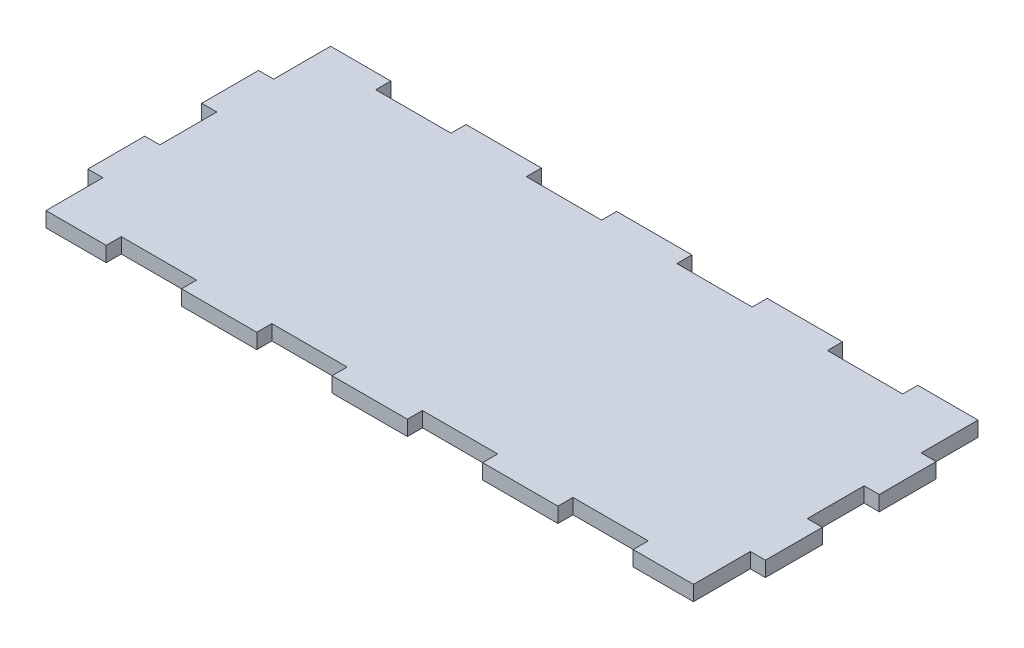
SolidWorks part; units mm, degrees
ref_plane "Front Plane" through (0, 0, 0) normal (0, 0, 1) x (1, 0, 0)
ref_plane "Top Plane" through (0, 0, 0) normal (0, 1, 0) x (1, 0, 0)
ref_plane "Right Plane" through (0, 0, 0) normal (1, 0, 0) x (0, 0, -1)
sketch "Sketch1" plane through (0, 0, 0) normal (0, 1, 0) x (1, 0, 0)
  line L1 (-57.15, 24.003) -> (57.15, 24.003)
  line L2 (-57.15, 24.003) -> (-57.15, -24.003)
  line L3 (-57.15, -24.003) -> (57.15, -24.003)
  line L4 (57.15, 24.003) -> (57.15, -24.003)
  line L5 (-57.15, 24.003) -> (57.15, -24.003) construction
  line L6 (-57.15, -24.003) -> (57.15, 24.003) construction
  point P0 (0, 0)
  dimension "D1" = 48.006
  dimension "D2" = 114.3
extrude "Boss-Extrude1" add sketch "Sketch1" along normal blind 2.54
sketch "Sketch2" plane through (0, 2.54, 0) normal (0, 1, 0) x (1, 0, 0)
  line L0 (57.15, -14.4018) -> (54.61, -14.4018)
  line L1 (57.15, -24.003) -> (57.15, 24.003) construction
  line L2 (54.61, -14.4018) -> (54.61, -24.003)
  line L3 (54.61, -24.003) -> (44.45, -24.003)
  line L4 (44.45, -24.003) -> (44.45, -21.463)
  line L5 (44.45, -21.463) -> (31.75, -21.463)
  line L6 (31.75, -21.463) -> (31.75, -24.003)
  line L7 (-57.15, -24.003) -> (57.15, -24.003) construction
  line L8 (31.75, -24.003) -> (19.05, -24.003)
  line L9 (19.05, -24.003) -> (19.05, -21.463)
  line L10 (19.05, -21.463) -> (6.35, -21.463)
  line L11 (6.35, -21.463) -> (6.35, -24.003)
  line L12 (6.35, -24.003) -> (-6.35, -24.003)
  line L13 (-6.35, -24.003) -> (-6.35, -21.463)
  line L14 (-6.35, -21.463) -> (-19.05, -21.463)
  line L15 (-19.05, -21.463) -> (-19.05, -24.003)
  line L16 (-19.05, -24.003) -> (-31.75, -24.003)
  line L17 (-31.75, -24.003) -> (-31.75, -21.463)
  line L18 (-31.75, -21.463) -> (-44.45, -21.463)
  line L19 (-44.45, -21.463) -> (-44.45, -24.003)
  line L20 (-44.45, -24.003) -> (-54.61, -24.003)
  line L21 (-54.61, -24.003) -> (-54.61, -14.4018)
  line L22 (-54.61, -14.4018) -> (-57.15, -14.4018)
  line L23 (-57.15, 24.003) -> (-57.15, -24.003) construction
  line L24 (57.15, -14.4018) -> (57.15, -4.8006)
  line L25 (57.15, -4.8006) -> (54.61, -4.8006)
  line L26 (54.61, -4.8006) -> (54.61, 4.8006)
  line L27 (54.61, 4.8006) -> (57.15, 4.8006)
  line L28 (57.15, 4.8006) -> (57.15, 14.4018)
  line L29 (57.15, 14.4018) -> (54.61, 14.4018)
  line L30 (54.61, 14.4018) -> (54.61, 24.003)
  line L31 (-57.15, -14.4018) -> (-57.15, -4.8006)
  line L32 (-57.15, -4.8006) -> (-54.61, -4.8006)
  line L33 (-54.61, -4.8006) -> (-54.61, 4.8006)
  line L34 (-54.61, 4.8006) -> (-57.15, 4.8006)
  line L35 (-57.15, 4.8006) -> (-57.15, 14.4018)
  line L36 (-57.15, 14.4018) -> (-54.61, 14.4018)
  line L37 (-54.61, 14.4018) -> (-54.61, 24.003)
  line L38 (57.15, 24.003) -> (-57.15, 24.003) construction
  line L39 (54.61, 24.003) -> (44.45, 24.003)
  line L40 (44.45, 24.003) -> (44.45, 21.463)
  line L41 (44.45, 21.463) -> (31.75, 21.463)
  line L42 (31.75, 21.463) -> (31.75, 24.003)
  line L43 (31.75, 24.003) -> (19.05, 24.003)
  line L44 (19.05, 24.003) -> (19.05, 21.463)
  line L45 (19.05, 21.463) -> (6.35, 21.463)
  line L46 (6.35, 21.463) -> (6.35, 24.003)
  line L47 (6.35, 24.003) -> (-6.35, 24.003)
  line L48 (-6.35, 24.003) -> (-6.35, 21.463)
  line L49 (-6.35, 21.463) -> (-19.05, 21.463)
  line L50 (-19.05, 21.463) -> (-19.05, 24.003)
  line L51 (-19.05, 24.003) -> (-31.75, 24.003)
  line L52 (-31.75, 24.003) -> (-31.75, 21.463)
  line L53 (-31.75, 21.463) -> (-44.45, 21.463)
  line L54 (-44.45, 21.463) -> (-44.45, 24.003)
  line L55 (-44.45, 24.003) -> (-54.61, 24.003)
  point P34 (-55.7135, 19.8563)
  point P43 (0, 0)
  point P44 (0, 0)
  point P45 (-51.1216, 18.9196)
  point P65 (0, 0)
  point P66 (0, 0)
  point P67 (0, 0)
  line M11 (57.15, -24.003) -> (57.15, 24.003)
  line M12 (57.15, 24.003) -> (-57.15, 24.003)
  line M13 (-57.15, 24.003) -> (-57.15, -24.003)
  line M14 (-57.15, -24.003) -> (57.15, -24.003)
  dimension "D1" = 9.6012
  dimension "D2" = 2.54
  dimension "D3" = 2.54
  dimension "D4" = 12.7
  dimension "D5" = 9.6012
  dimension "D6" = 2.54
  dimension "D7" = 2.54
  dimension "D8" = 12.7
  dimension "D9" = 2.54
extrude "Cut-Extrude2" cut sketch "Sketch2" against normal up to next contours L36 L37 M12 M13 | L54 L53 L52 M12 | L50 L49 L48 M12 | L46 L45 L44 M12 | L42 L41 L40 M12 | L30 L29 M11 M12 | L27 L26 L25 M11 | L0 L2 M14 M11 | L5 L6 L4 M14 | L10 L11 L9 M14 | L14 L15 L13 M14 | L18 L19 L17 M14 | L21 L22 M13 M14 | L33 L34 L32 M13
